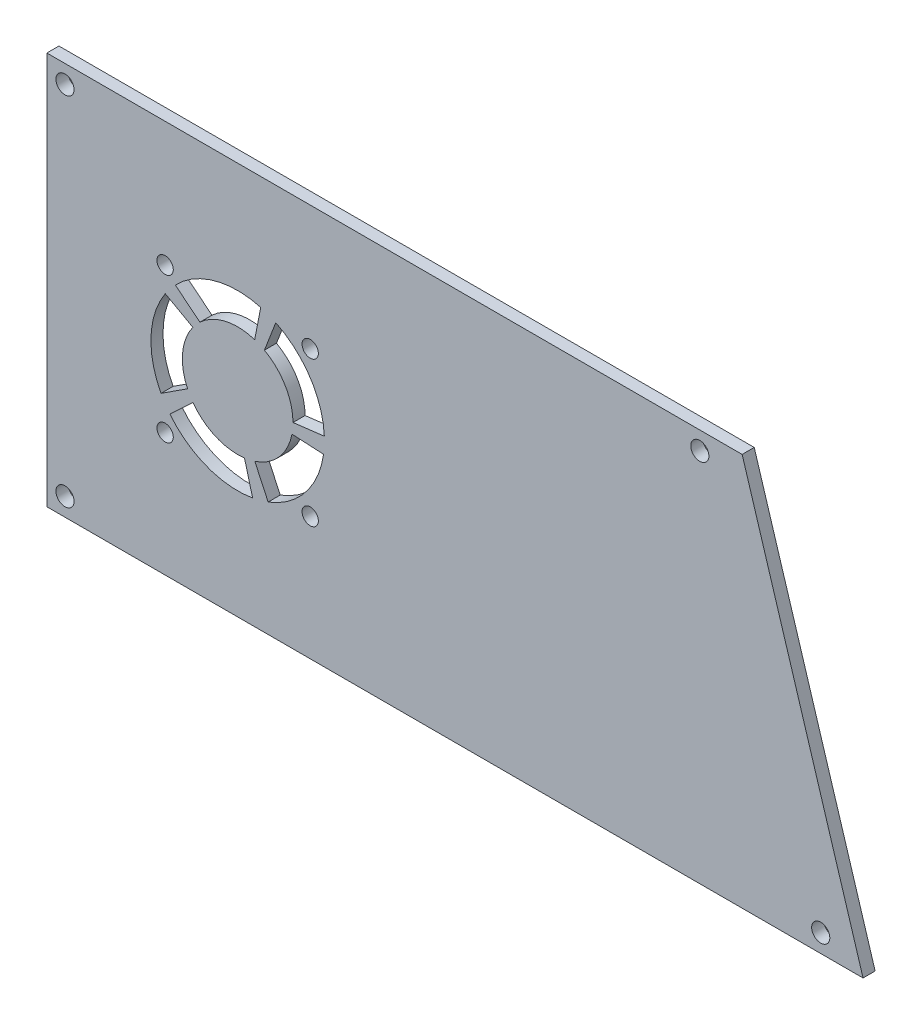
SolidWorks part; units mm, degrees
ref_plane "Alzado" through (0, 0, 0) normal (0, 0, 1) x (1, 0, 0)
ref_plane "Planta" through (0, 0, 0) normal (0, 1, 0) x (1, 0, 0)
ref_plane "Vista lateral" through (0, 0, 0) normal (1, 0, 0) x (0, 0, -1)
sketch "Croquis1" plane through (0, 0, 0) normal (0, 0, 1) x (1, 0, 0)
  line L1 (-57.5, -32.5) -> (57.5, -32.5)
  line L2 (-57.5, -32.5) -> (-57.5, 32.5)
  line L3 (-57.5, 32.5) -> (57.5, 32.5)
  line L4 (57.5, -32.5) -> (57.5, 32.5)
  line L5 (-57.5, -32.5) -> (57.5, 32.5) construction
  line L6 (-57.5, 32.5) -> (57.5, -32.5) construction
  point P0 (0, 0)
  dimension "D1" = 115
  dimension "D2" = 65
extrude "Saliente-Extruir1" add sketch "Croquis1" along normal blind 2
sketch "Croquis2" plane through (0, 0, 0) normal (0, 0, -1) x (-1, 0, 0)
  line L0 (-57.5, 32.5) -> (-77.5, -32.5)
  line L1 (-77.5, -32.5) -> (-57.5, -32.5)
  line L2 (-57.5, -32.5) -> (-57.5, 32.5)
extrude "Saliente-Extruir2" add sketch "Croquis2" against normal blind 2
sketch "Croquis3" plane through (0, 0, 0) normal (0, 0, -1) x (-1, 0, 0)
  circle A0 centre (-50.5, 29.5) radius 1.5
  circle A1 centre (-70.5, -29.5) radius 1.5
  circle A2 centre (54.5, -29.5) radius 1.5
  circle A3 centre (54.5, 29.5) radius 1.5
extrude "Cortar-Extruir1" cut sketch "Croquis3" against normal blind 2
sketch "Croquis4" plane through (0, 0, 0) normal (0, 0, -1) x (-1, 0, 0)
  circle A0 centre (13.9403, 11.9106) radius 1.35
  circle A1 centre (37.9403, 11.9106) radius 1.35
  circle A2 centre (37.9403, -12.0894) radius 1.35
  circle A3 centre (13.9403, -12.0894) radius 1.35
  circle A5 centre (25.9403, -0.0894) radius 9.15
  circle A6 centre (25.9403, -0.0894) radius 14.35
  dimension "D1" = 2.7
  dimension "D2" = 2.7
  dimension "D3" = 2.7
  dimension "D4" = 2.7
extrude "Cortar-Extruir3" cut sketch "Croquis4" against normal blind 2
sketch "Croquis5" plane through (0, 0, 2) normal (0, 0, 1) x (1, 0, 0)
  line L0 (-38.6184, -6.8117) -> (-34.2278, -3.9676)
  line L1 (-37.1593, -9.0368) -> (-33.3348, -5.4786)
  circle A0 centre (-25.9403, -0.0894) radius 14.35 construction
  circle A1 centre (-25.9403, -0.0894) radius 9.15 construction
  circle A2 centre (-25.9403, -0.0894) radius 1.3669
  arc A3 (-33.3348, -5.4786) -> (-34.2278, -3.9676) centre (-25.9403, -0.0894) cw
  arc A4 (-37.1593, -9.0368) -> (-38.6184, -6.8117) centre (-25.9403, -0.0894) cw
  dimension "D1" = 10
extrude "Saliente-Extruir3" add sketch "Croquis5" against normal blind 2
pattern_circular "MatrizC1" count 5 every 72 about axis through (-25.9403, -0.0894, 0) along (0, 0, 1) of "Saliente-Extruir3"
